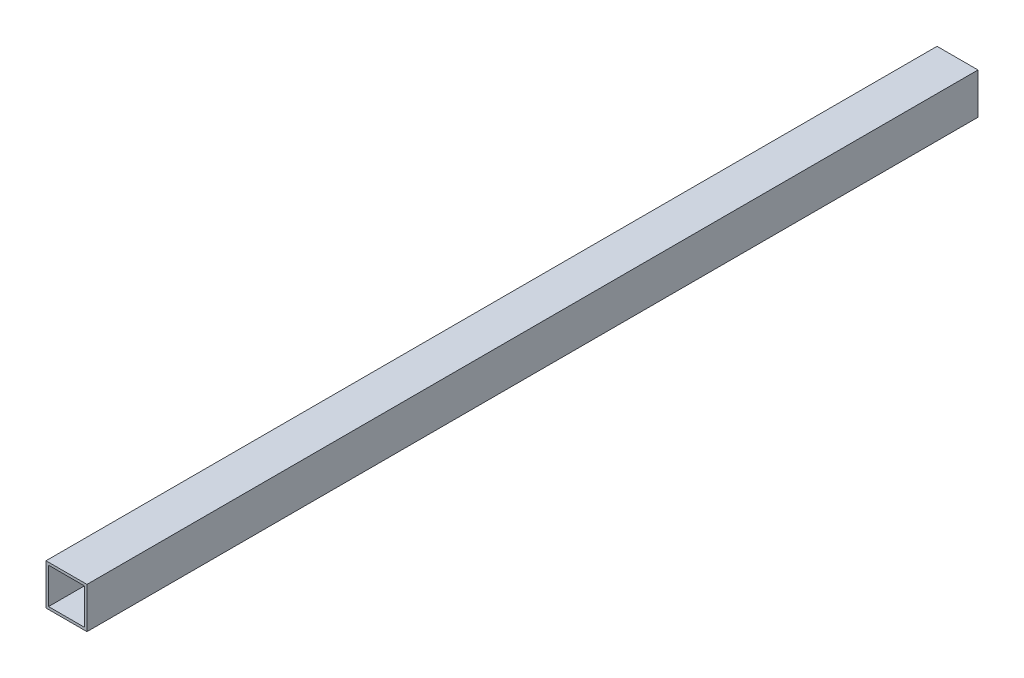
SolidWorks part; units mm, degrees
ref_plane "Front Plane" through (0, 0, 0) normal (0, 0, 1) x (1, 0, 0)
ref_plane "Top Plane" through (0, 0, 0) normal (0, 1, 0) x (1, 0, 0)
ref_plane "Right Plane" through (0, 0, 0) normal (1, 0, 0) x (0, 0, -1)
sketch "Sketch1" plane through (0, 0, 0) normal (0, 0, 1) x (1, 0, 0)
  line L1 (-25.4, 25.4) -> (25.4, 25.4)
  line L2 (-25.4, 25.4) -> (-25.4, -25.4)
  line L3 (-25.4, -25.4) -> (25.4, -25.4)
  line L4 (25.4, 25.4) -> (25.4, -25.4)
  line L5 (-25.4, 25.4) -> (25.4, -25.4) construction
  line L6 (-25.4, -25.4) -> (25.4, 25.4) construction
  line L7 (-22.225, 22.225) -> (22.225, 22.225)
  line L8 (-22.225, 22.225) -> (-22.225, -22.225)
  line L9 (-22.225, -22.225) -> (22.225, -22.225)
  line L10 (22.225, 22.225) -> (22.225, -22.225)
  line L11 (-22.225, 22.225) -> (22.225, -22.225) construction
  line L12 (-22.225, -22.225) -> (22.225, 22.225) construction
  point P0 (0, 0)
  point P6 (0, 0)
  dimension "D1" = 50.8
  dimension "D2" = 50.8
  dimension "D3" = 3.175
extrude "Boss-Extrude1" add sketch "Sketch1" against normal blind 1104.9
